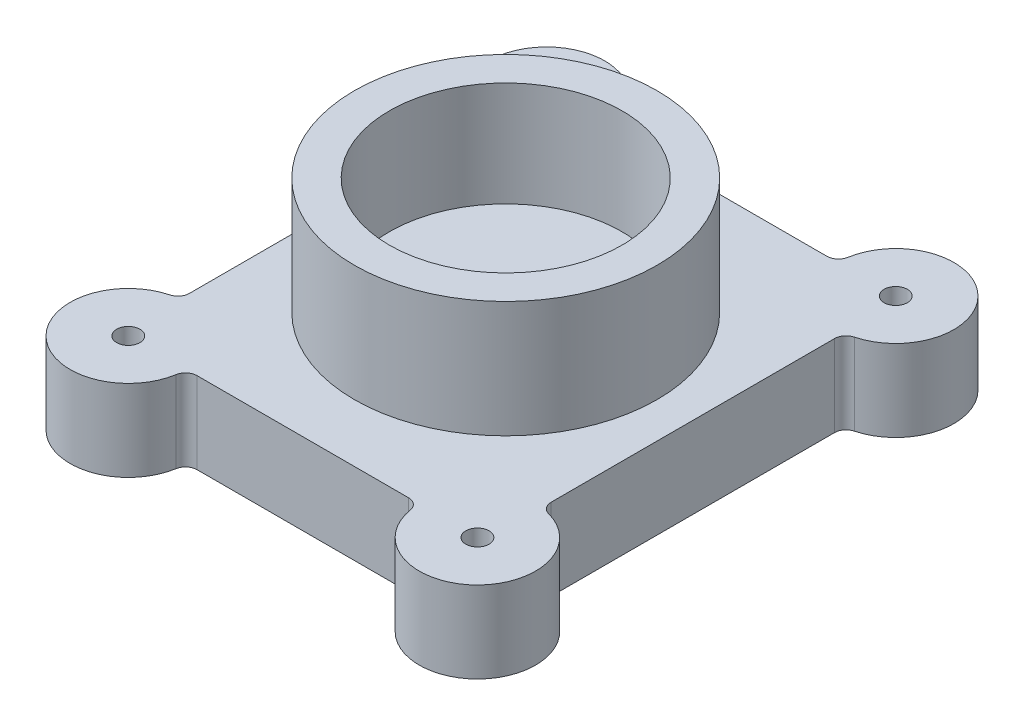
SolidWorks part; units mm, degrees
material "AISI 1020 Steel, Cold Rolled"
ref_plane "Front Plane" through (0, 0, 0) normal (0, 0, 1) x (1, 0, 0)
ref_plane "Top Plane" through (0, 0, 0) normal (0, 1, 0) x (1, 0, 0)
ref_plane "Right Plane" through (0, 0, 0) normal (1, 0, 0) x (0, 0, -1)
sketch "Sketch1" plane through (0, 0, 0) normal (0, 1, 0) x (1, 0, 0)
  line L1 (-150, 0) -> (-172.1087, 0) construction
  line L3 (-85.4508, 179.7088) -> (96.2276, 179.7088)
  line L7 (-150, -121.7157) -> (-150, 121.7157)
  line L9 (-85.4508, -179.7088) -> (96.2276, -179.7088)
  line L10 (5.3884, -179.7088) -> (5.3884, -152.7563) construction
  line L11 (160.7768, -121.7157) -> (160.7768, 121.7157)
  arc A1 (-95.3109, 188.0421) -> (-157.4353, 131.3812) centre (-144.6116, 179.7088) ccw
  arc A2 (-150, 121.7157) -> (-157.4353, 131.3812) centre (-160, 121.7157) ccw
  arc A3 (-95.3109, 188.0421) -> (-85.4508, 179.7088) centre (-85.4508, 189.7088) ccw
  arc A4 (-95.3109, -188.0421) -> (-85.4508, -179.7088) centre (-85.4508, -189.7088) cw
  arc A5 (-150, -121.7157) -> (-157.4353, -131.3812) centre (-160, -121.7157) cw
  arc A6 (-95.3109, -188.0421) -> (-157.4353, -131.3812) centre (-144.6116, -179.7088) cw
  arc A7 (106.0878, -188.0421) -> (96.2276, -179.7088) centre (96.2276, -189.7088) ccw
  arc A8 (106.0878, -188.0421) -> (168.2121, -131.3812) centre (155.3884, -179.7088) ccw
  arc A9 (160.7768, -121.7157) -> (168.2121, -131.3812) centre (170.7768, -121.7157) ccw
  arc A10 (160.7768, 121.7157) -> (168.2121, 131.3812) centre (170.7768, 121.7157) cw
  arc A11 (106.0878, 188.0421) -> (168.2121, 131.3812) centre (155.3884, 179.7088) cw
  arc A12 (106.0878, 188.0421) -> (96.2276, 179.7088) centre (96.2276, 189.7088) cw
  point P11 (-150, 130)
  point P15 (-94.6116, 179.7088)
  point P24 (-150, 0)
  point P25 (5.3884, -179.7088)
  point P39 (5.3884, 179.7088)
  dimension "D3" = 100
  dimension "D4" = 130
  dimension "D5" = 10
  dimension "D6" = 10
extrude "Boss-Extrude1" add sketch "Sketch1" along normal blind 70 contours L9 A7 A8 A9 L11 A10 A11 A12 L3 A3 A1 A2 L7 A5 A6 A4
sketch "Sketch2" plane through (0, 70, 0) normal (0, 1, 0) x (1, 0, 0)
  circle A0 centre (0, 0) radius 130
extrude "Boss-Extrude2" add sketch "Sketch2" along normal blind 100
sketch "Sketch5" plane through (0, 70, 0) normal (0, 1, 0) x (1, 0, 0)
  circle A0 centre (-144.6116, -179.7088) radius 10
  circle A2 centre (-144.6116, 179.7088) radius 10
  circle A3 centre (155.3884, -179.7088) radius 10
  circle A4 centre (155.3884, 179.7088) radius 10
  dimension "D1" = 20
  dimension "D2" = 20
  dimension "D3" = 20
  dimension "D4" = 20
extrude "Cut-Extrude1" cut sketch "Sketch5" against normal through all
sketch "Sketch6" plane through (0, 170, 0) normal (0, 1, 0) x (1, 0, 0)
  circle A0 centre (0, 0) radius 100
extrude "Cut-Extrude2" cut sketch "Sketch6" against normal blind 90
